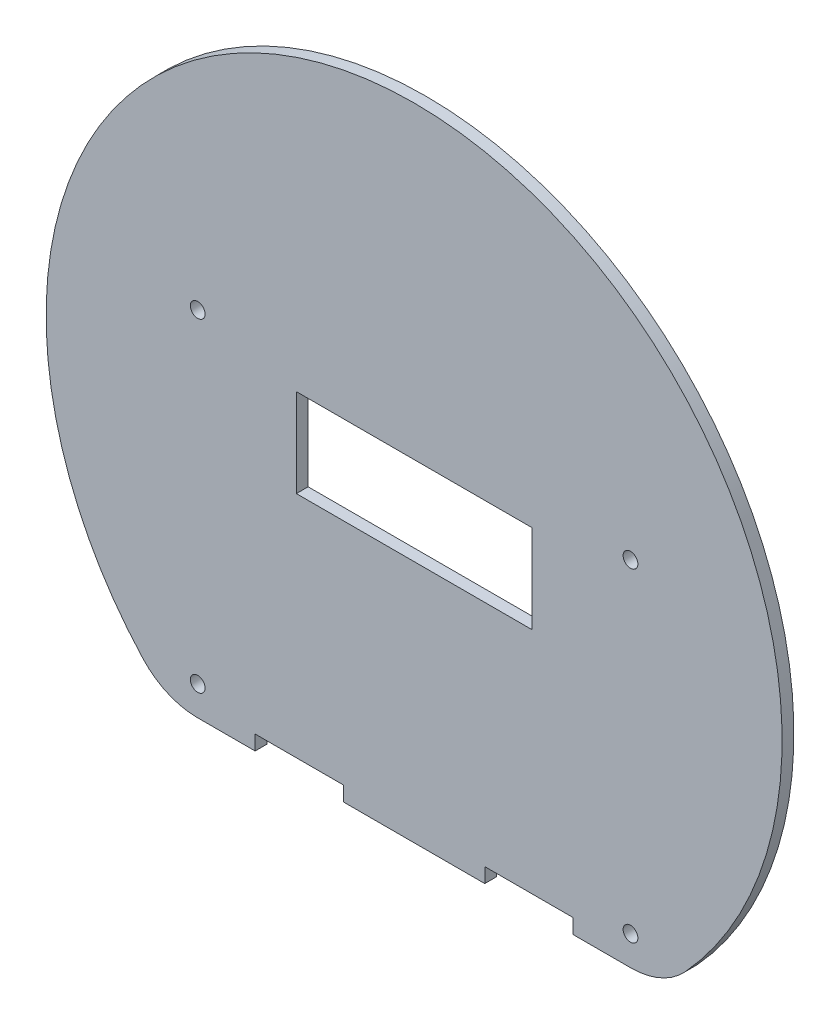
SolidWorks part; units mm, degrees
ref_plane "Front Plane" through (0, 0, 0) normal (0, 0, 1) x (1, 0, 0)
ref_plane "Top Plane" through (0, 0, 0) normal (0, 1, 0) x (1, 0, 0)
ref_plane "Right Plane" through (0, 0, 0) normal (1, 0, 0) x (0, 0, -1)
sketch "Sketch1" plane through (0, 0, 0) normal (0, 0, 1) x (1, 0, 0)
  line L3 (0, 125) -> (0, -125) construction
  circle A4 centre (0, 0) radius 125
  dimension "D1" = 250
extrude "Boss-Extrude1" add sketch "Sketch1" along normal blind 4
sketch "Sketch2" plane through (0, 0, 4) normal (0, 0, 1) x (1, 0, 0)
  circle A0 centre (0, 92.9904) radius 1.5
  circle A1 centre (11.25, 73.5048) radius 1.5
  circle A2 centre (-11.25, 73.5048) radius 1.5
  dimension "D1" = 3
extrude "Cut-Extrude1" [suppressed] cut sketch "Sketch2" against normal blind 10
sketch "Sketch3" plane through (0, 0, 4) normal (0, 0, 1) x (1, 0, 0)
  line L0 (-83.9155, -92.6455) -> (83.9155, -92.6455)
  arc A1 (-83.9155, -92.6455) -> (83.9155, -92.6455) centre (0, 0) ccw
extrude "Cut-Extrude2" cut sketch "Sketch3" against normal blind 10
fillet "Fillet1" radius 25 2 edges at (83.9155, -92.6455, 2) (-83.9155, -92.6455, 2)
sketch "Sketch6" plane through (0, 0, 4) normal (0, 0, 1) x (1, 0, 0)
  line L0 (73.6484, -92.6455) -> (-73.6484, -92.6455) construction
  line L1 (24, -92.6455) -> (54, -92.6455)
  line L2 (24, -92.6455) -> (24, -87.6455)
  line L3 (24, -87.6455) -> (54, -87.6455)
  line L4 (54, -92.6455) -> (54, -87.6455)
  line L5 (0, 0) -> (0, -92.6455) construction
  line L6 (-54, -92.6455) -> (-54, -87.6455)
  line L7 (-24, -87.6455) -> (-54, -87.6455)
  line L8 (-24, -92.6455) -> (-24, -87.6455)
  line L9 (-24, -92.6455) -> (-54, -92.6455)
  arc A0 (92.0605, -84.5568) -> (-92.0605, -84.5568) centre (0, 0) ccw construction
  dimension "D1" = 30
  dimension "D2" = 54
  dimension "D3" = 5
extrude "Cut-Extrude5" cut sketch "Sketch6" against normal blind 5
sketch "Sketch7" plane through (0, 0, 4) normal (0, 0, 1) x (1, 0, 0)
  circle A0 centre (73.5, -82.6455) radius 2.5
  circle A1 centre (73.5, 27.3545) radius 2.5
  circle A2 centre (-73.5, 27.3545) radius 2.5
  circle A3 centre (-73.5, -82.6455) radius 2.5
  dimension "D1" = 5
extrude "Cut-Extrude6" cut sketch "Sketch7" against normal through all
sketch "Sketch8" plane through (0, 0, 4) normal (0, 0, 1) x (1, 0, 0)
  line L1 (-40, 20.0745) -> (40, 20.0745)
  line L2 (-40, 20.0745) -> (-40, -9.9255)
  line L3 (-40, -9.9255) -> (40, -9.9255)
  line L4 (40, 20.0745) -> (40, -9.9255)
  line L5 (-40, 20.0745) -> (40, -9.9255) construction
  line L6 (-40, -9.9255) -> (40, 20.0745) construction
  point P0 (0, 5.0745)
  dimension "D1" = 80
  dimension "D2" = 30
extrude "Cut-Extrude7" cut sketch "Sketch8" against normal through all
